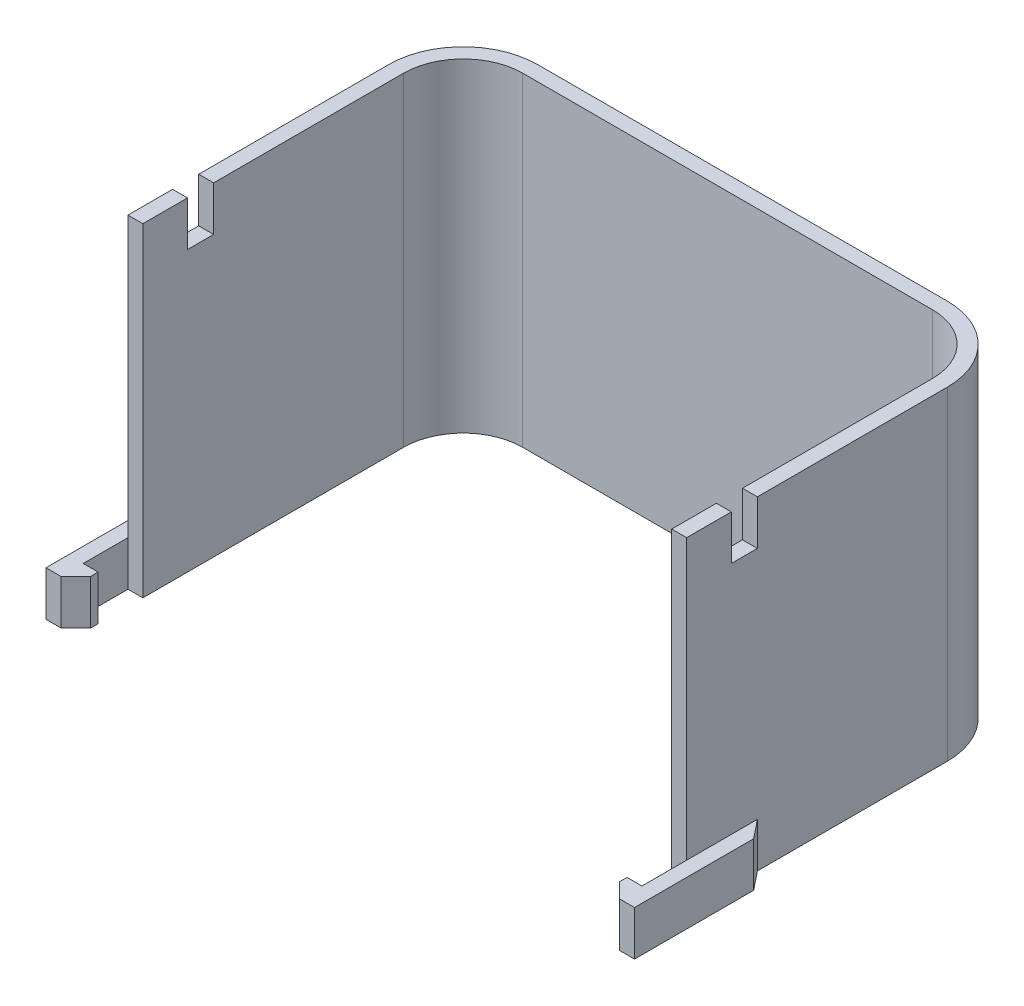
SolidWorks part; units mm, degrees
ref_plane "Front Plane" through (0, 0, 0) normal (0, 0, 1) x (1, 0, 0)
ref_plane "Top Plane" through (0, 0, 0) normal (0, 1, 0) x (1, 0, 0)
ref_plane "Right Plane" through (0, 0, 0) normal (1, 0, 0) x (0, 0, -1)
sketch "Sketch2" plane through (0, 0, 0) normal (0, 1, 0) x (1, 0, 0)
  line L0 (35.3932, 0) -> (37.3932, 0)
  line L1 (-37.6068, 0) -> (-35.6068, 0)
  line L2 (-37.6068, 0) -> (-37.6068, 45)
  line L3 (-37.6068, 45) -> (37.3932, 45)
  line L4 (37.3932, 0) -> (37.3932, 45)
  line L5 (-35.6068, 43) -> (35.3932, 43)
  line L6 (-35.6068, 43) -> (-35.6068, 0)
  line L8 (35.3932, 43) -> (35.3932, 0)
  dimension "D1" = 75
  dimension "D2" = 45
  dimension "D3" = 2
  dimension "D4" = 2
  dimension "D5" = 2
extrude "Boss-Extrude1" add sketch "Sketch2" along normal blind 43.5
fillet "Fillet1" radius 8 2 edges at (35.3932, 21.75, -43) (-35.6068, 21.75, -43)
fillet "Fillet2" radius 10 2 edges at (-37.6068, 21.75, -45) (37.3932, 21.75, -45)
sketch "Sketch3" plane through (0, 0, 0) normal (1, 0, 0) x (0, 0, -1)
  line L0 (0, 43.5) -> (35, 43.5) construction
  line L1 (6, 43.5) -> (9.5, 43.5)
  line L2 (6, 43.5) -> (6, 37.5)
  line L3 (6, 37.5) -> (9.5, 37.5)
  line L4 (9.5, 43.5) -> (9.5, 37.5)
  line L5 (0, 43.5) -> (0, 0) construction
  dimension "D1" = 6
  dimension "D2" = 3.5
  dimension "D3" = 6
extrude "Cut-Extrude1" cut sketch "Sketch3" against normal mid plane 115.5
sketch "Sketch4" plane through (0, 0, 0) normal (0, -1, 0) x (1, 0, 0)
  line L0 (-37.6068, -35) -> (-37.6068, 0) construction
  line L2 (-37.6068, -7) -> (-37.6068, 6)
  line L3 (-37.6068, 9) -> (-39.6068, 9)
  line L4 (-39.6068, -7) -> (-39.6068, 9)
  line L6 (-39.6068, -7) -> (-37.6068, -9.5)
  line L7 (-37.6068, -9.5) -> (-37.6068, -7)
  line L8 (-37.6068, 0) -> (-35.6068, 0) construction
  line L9 (-37.6068, 9) -> (-35.6068, 7)
  line L10 (-35.6068, 7) -> (-35.6068, 6)
  line L11 (-35.6068, 6) -> (-37.6068, 6)
  line L12 (37.3932, 0) -> (37.3932, -35) construction
  line L14 (37.3932, -7) -> (37.3932, 6)
  line L15 (37.3932, 9) -> (39.3932, 9)
  line L16 (39.3932, -7) -> (39.3932, 9)
  line L17 (35.3932, 0) -> (37.3932, 0) construction
  line L18 (39.3932, -7) -> (37.3932, -9.5)
  line L19 (37.3932, -9.5) -> (37.3932, -7)
  line L20 (37.3932, 9) -> (35.3932, 7)
  line L21 (35.3932, 7) -> (35.3932, 6)
  line L22 (35.3932, 6) -> (37.3932, 6)
  dimension "D1" = 9.5
  dimension "D2" = 2
  dimension "D3" = 9
  dimension "D4" = 6
  dimension "D5" = 1
  dimension "D6" = 9.5
  dimension "D7" = 7
  dimension "D8" = 2
  dimension "D9" = 9
  dimension "D10" = 6
  dimension "D11" = 2
  dimension "D12" = 2
  dimension "D13" = 1
extrude "Boss-Extrude2" add sketch "Sketch4" against normal blind 6
